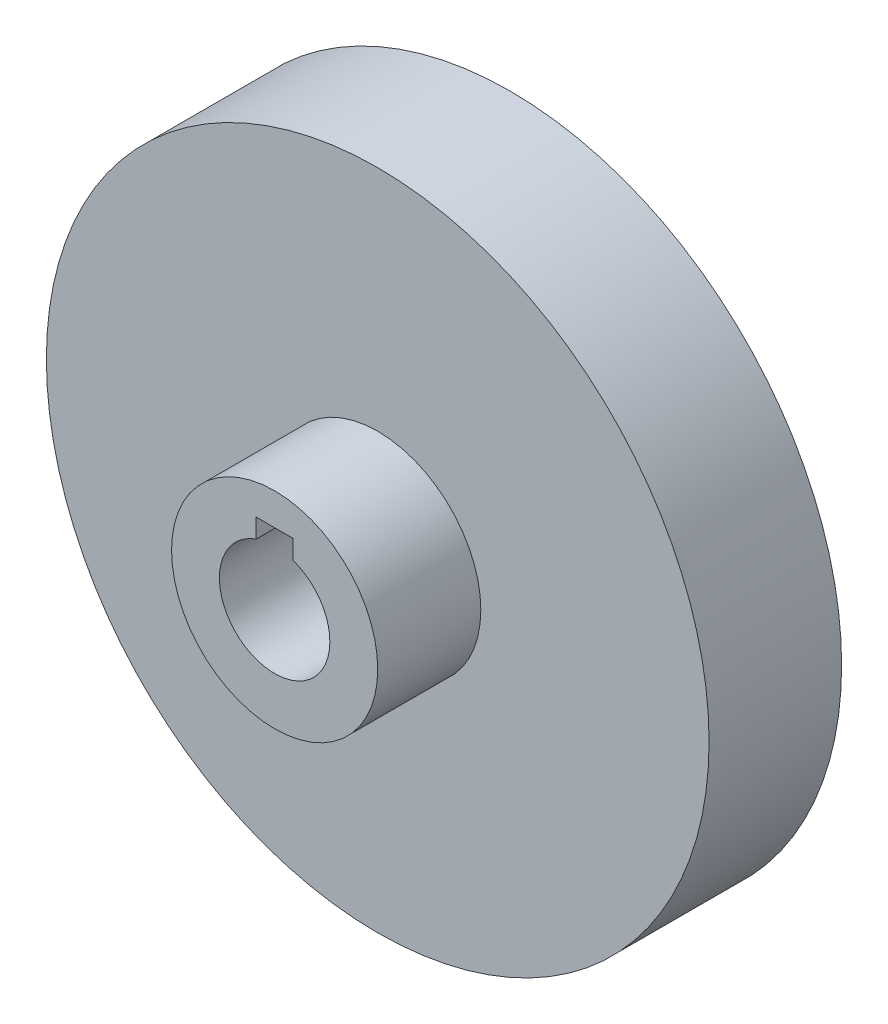
SolidWorks part; units mm, degrees
ref_plane "Front Plane" through (0, 0, 0) normal (0, 0, 1) x (1, 0, 0)
ref_plane "Top Plane" through (0, 0, 0) normal (0, 1, 0) x (1, 0, 0)
ref_plane "Right Plane" through (0, 0, 0) normal (1, 0, 0) x (0, 0, -1)
sketch "Sketch1" plane through (0, 0, 0) normal (1, 0, 0) x (0, 0, -1)
  line L0 (-42.784, 0) -> (44.128, 0) construction
  line L1 (-23, 7.5) -> (-23, 14)
  line L2 (-23, 14) -> (-9, 14)
  line L3 (-9, 14) -> (-9, 45)
  line L4 (-9, 45) -> (9, 45)
  line L5 (9, 45) -> (9, 14)
  line L6 (9, 14) -> (12, 14)
  line L7 (12, 14) -> (12, 7.5)
  line L8 (12, 7.5) -> (-23, 7.5)
  point P12 (0, 45)
  dimension "D1" = 14
  dimension "D2" = 7.5
  dimension "D3" = 18
  dimension "D4" = 35
  dimension "D5" = 3
  dimension "D6" = 45
revolve "Revolve1" add sketch "Sketch1" angle 360 about L0
sketch "Sketch2" plane through (0, 0, 0) normal (1, 0, 0) x (0, 0, -1)
  line L0 (-23, 9.65) -> (-23, 5)
  line L1 (-23, 5) -> (12, 5)
  line L2 (12, 5) -> (12, 10)
  line L3 (12, 10) -> (-23, 9.65)
  point P4 (12, 7.5)
  dimension "D1" = 5
  dimension "D2" = 35
  dimension "D3" = 4.65
extrude "Cut-Extrude1" cut sketch "Sketch2" against normal mid plane 5
